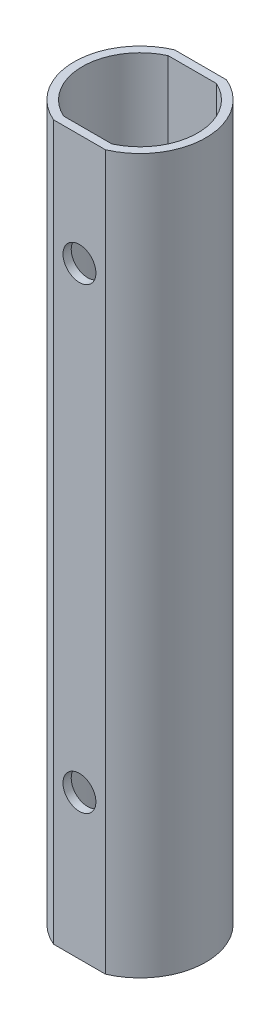
SolidWorks part; units mm, degrees
material "6061-T6 (SS)"
ref_plane "Front Plane" through (0, 0, 0) normal (0, 0, 1) x (1, 0, 0)
ref_plane "Top Plane" through (0, 0, 0) normal (0, 1, 0) x (1, 0, 0)
ref_plane "Right Plane" through (0, 0, 0) normal (1, 0, 0) x (0, 0, -1)
sketch "Sketch1" plane through (0, 0, 0) normal (0, 1, 0) x (1, 0, 0)
  line L2 (-4.663, -10.0868) -> (4.663, -10.0868)
  line L3 (-12.7, 0) -> (-11.1125, 0) construction
  line L4 (0, -10.0868) -> (0, -11.6743) construction
  line L5 (-5, -11.6743) -> (5, -11.6743)
  line L6 (-4.663, 10.0868) -> (4.663, 10.0868)
  line L7 (-5, 11.6743) -> (5, 11.6743)
  arc A0 (5, -11.6743) -> (5, 11.6743) centre (0, 0) ccw
  arc A1 (4.663, -10.0868) -> (4.663, 10.0868) centre (0, 0) ccw
  arc A2 (-5, 11.6743) -> (-5, -11.6743) centre (0, 0) ccw
  arc A3 (-4.663, 10.0868) -> (-4.663, -10.0868) centre (0, 0) ccw
  dimension "D1" = 25.4
  dimension "D2" = 1.5875
  dimension "D3" = 10
extrude "Boss-Extrude1" add sketch "Sketch1" along normal blind 137.66
sketch "Sketch2" plane through (0, 0, -11.6743) normal (0, 0, -1) x (-1, 0, 0)
  line L0 (-5, 137.66) -> (5, 137.66) construction
  line L1 (5, 137.66) -> (5, 0) construction
  circle A0 centre (0, 27.85) radius 3.175
  circle A1 centre (0, 116.16) radius 3.175
  dimension "D1" = 6.35
  dimension "D2" = 6.35
  dimension "D3" = 27.85
  dimension "D4" = 21.5
  dimension "D5" = 5
  dimension "D6" = 5
extrude "Cut-Extrude1" cut sketch "Sketch2" against normal up to surface (23.3487 mm away) up to face at (0, 68.83, 11.6743)
